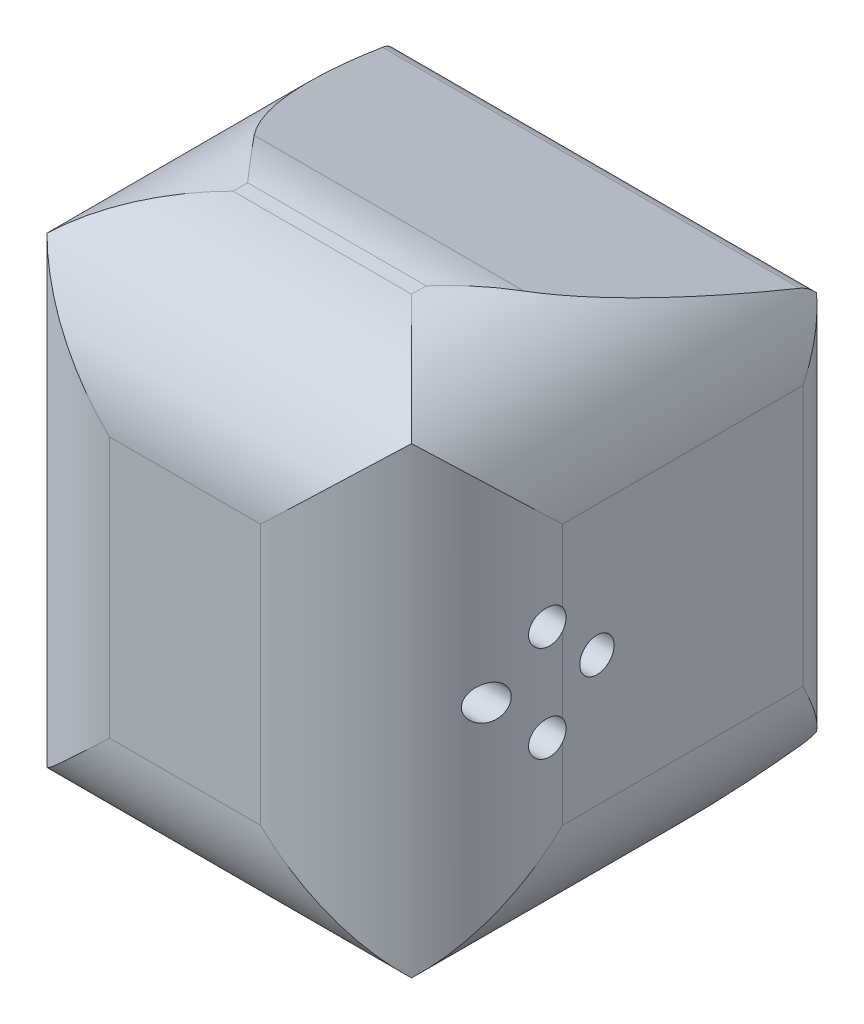
SolidWorks part; units mm, degrees
ref_plane "Front Plane" through (0, 0, 0) normal (0, 0, 1) x (1, 0, 0)
ref_plane "Top Plane" through (0, 0, 0) normal (0, 1, 0) x (1, 0, 0)
ref_plane "Right Plane" through (0, 0, 0) normal (1, 0, 0) x (0, 0, -1)
ref_plane "PX_m33_000" through (-33, 0, 0) normal (1, 0, 0) x (0, 0, -1)
sketch "S_prism1" plane through (-33, 0, 0) normal (1, 0, 0) x (0, 0, -1)
  line L0 (0, -25.0397) -> (0, 25.0397)
  line L1 (-2.8311, 28.8651) -> (-32.2859, 37.8651)
  line L2 (-39.8836, 39) -> (-42, 39)
  line L3 (-62, 19) -> (-62, -19)
  line L4 (-42, -39) -> (-39.8836, -39)
  line L5 (-32.2859, -37.8651) -> (-2.8311, -28.8651)
  arc A0 (-2.8311, -28.8651) -> (0, -25.0397) centre (-4.0002, -25.0395) ccw
  arc A1 (0, 25.0397) -> (-2.8311, 28.8651) centre (-4.0002, 25.0395) ccw
  arc A2 (-32.2859, 37.8651) -> (-39.8836, 39) centre (-39.8837, 12.9999) ccw
  arc A3 (-42, 39) -> (-62, 19) centre (-41.9999, 18.9999) ccw
  arc A4 (-62, -19) -> (-42, -39) centre (-41.9999, -18.9999) ccw
  arc A5 (-39.8836, -39) -> (-32.2859, -37.8651) centre (-39.8837, -12.9999) ccw
extrude "Boss_1" add sketch "S_prism1" along normal blind 66
ref_plane "PY_m40_000" through (0, -40, 0) normal (0, 1, 0) x (1, 0, 0)
sketch "S_pcut2" plane through (0, -40, 0) normal (0, 1, 0) x (1, 0, 0)
  line L0 (33.6, -62.6) -> (11, -62.6)
  line L1 (11, -62.6) -> (11, -62)
  line L2 (33, -40) -> (33.6, -40)
  line L3 (33.6, -40) -> (33.6, -62.6)
  arc A0 (11, -62) -> (33, -40) centre (10.9998, -39.9998) ccw
extrude "Cut_2" cut sketch "S_pcut2" along normal blind 80
sketch "S_pcut3" plane through (0, -40, 0) normal (0, 1, 0) x (1, 0, 0)
  line L0 (-33.6, -62.6) -> (-11, -62.6)
  line L1 (-11, -62.6) -> (-11, -62)
  line L2 (-33, -40) -> (-33.6, -40)
  line L3 (-33.6, -40) -> (-33.6, -62.6)
  arc A0 (-11, -62) -> (-33, -40) centre (-10.9998, -39.9998) cw
extrude "Cut_3" cut sketch "S_pcut3" along normal blind 80
sketch "S_pcut4" plane through (0, -40, 0) normal (0, 1, 0) x (1, 0, 0)
  line L0 (33.6, 0.6) -> (28, 0.6)
  line L1 (28, 0.6) -> (28, 0)
  line L2 (33, -5) -> (33.6, -5)
  line L3 (33.6, -5) -> (33.6, 0.6)
  arc A0 (28, 0) -> (33, -5) centre (27.9999, -5.0001) cw
extrude "Cut_4" cut sketch "S_pcut4" along normal blind 80
sketch "S_pcut5" plane through (0, -40, 0) normal (0, 1, 0) x (1, 0, 0)
  line L0 (-33.6, 0.6) -> (-28, 0.6)
  line L1 (-28, 0.6) -> (-28, 0)
  line L2 (-33, -5) -> (-33.6, -5)
  line L3 (-33.6, -5) -> (-33.6, 0.6)
  arc A0 (-28, 0) -> (-33, -5) centre (-27.9999, -5.0001) ccw
extrude "Cut_5" cut sketch "S_pcut5" along normal blind 80
ref_plane "PZ_m0_100" through (0, 0, -0.1) normal (0, 0, 1) x (1, 0, 0)
sketch "S_pcut6" plane through (0, 0, -0.1) normal (0, 0, 1) x (1, 0, 0)
  line L0 (33.6, 39.6) -> (13, 39.6)
  line L1 (13, 39.6) -> (13, 39)
  line L2 (33, 19) -> (33.6, 19)
  line L3 (33.6, 19) -> (33.6, 39.6)
  arc A0 (13, 39) -> (33, 19) centre (12.9999, 18.9999) cw
extrude "Cut_6" cut sketch "S_pcut6" along normal blind 62.2
sketch "S_pcut7" plane through (0, 0, -0.1) normal (0, 0, 1) x (1, 0, 0)
  line L0 (33.6, -39.6) -> (13, -39.6)
  line L1 (13, -39.6) -> (13, -39)
  line L2 (33, -19) -> (33.6, -19)
  line L3 (33.6, -19) -> (33.6, -39.6)
  arc A0 (13, -39) -> (33, -19) centre (12.9999, -18.9999) ccw
extrude "Cut_7" cut sketch "S_pcut7" along normal blind 62.2
sketch "S_pcut8" plane through (0, 0, -0.1) normal (0, 0, 1) x (1, 0, 0)
  line L0 (-33.6, 39.6) -> (-13, 39.6)
  line L1 (-13, 39.6) -> (-13, 39)
  line L2 (-33, 19) -> (-33.6, 19)
  line L3 (-33.6, 19) -> (-33.6, 39.6)
  arc A0 (-13, 39) -> (-33, 19) centre (-12.9999, 18.9999) ccw
extrude "Cut_8" cut sketch "S_pcut8" along normal blind 62.2
sketch "S_pcut9" plane through (0, 0, -0.1) normal (0, 0, 1) x (1, 0, 0)
  line L0 (-33.6, -39.6) -> (-13, -39.6)
  line L1 (-13, -39.6) -> (-13, -39)
  line L2 (-33, -19) -> (-33.6, -19)
  line L3 (-33.6, -19) -> (-33.6, -39.6)
  arc A0 (-13, -39) -> (-33, -19) centre (-12.9999, -18.9999) cw
extrude "Cut_9" cut sketch "S_pcut9" along normal blind 62.2
sketch "S_cut10" plane through (0, 0, -0.1) normal (0, 0, 1) x (1, 0, 0)
  line L0 (-26, -24) -> (26, -24)
  line L1 (26, -24) -> (26, 24)
  line L2 (26, 24) -> (-26, 24)
  line L3 (-26, 24) -> (-26, -24)
  dimension "P1" = 26
  dimension "P2" = 24
  dimension "P3" = 26
  dimension "P4" = 24
  dimension "P5" = 26
  dimension "P6" = 24
  dimension "P7" = 26
  dimension "P8" = 24
extrude "Pocket_10" cut sketch "S_cut10" along normal blind 16.2
ref_plane "PZ_p16_000" through (0, 0, 16) normal (0, 0, 1) x (1, 0, 0)
sketch "S_cut11" plane through (0, 0, 16) normal (0, 0, 1) x (1, 0, 0)
  line L0 (-26, -30) -> (26, -30)
  line L1 (26, -30) -> (26, 30)
  line L2 (26, 30) -> (-26, 30)
  line L3 (-26, 30) -> (-26, -30)
  dimension "P1" = 26
  dimension "P2" = 30
  dimension "P3" = 26
  dimension "P4" = 30
  dimension "P5" = 26
  dimension "P6" = 30
  dimension "P7" = 26
  dimension "P8" = 30
extrude "Pocket_11" cut sketch "S_cut11" along normal blind 36
ref_plane "PZ_p51_900" through (0, 0, 51.9) normal (0, 0, 1) x (1, 0, 0)
sketch "S_cut12" plane through (0, 0, 51.9) normal (0, 0, 1) x (1, 0, 0)
  line L0 (-18, -24) -> (18, -24)
  line L1 (18, -24) -> (18, 24)
  line L2 (18, 24) -> (-18, 24)
  line L3 (-18, 24) -> (-18, -24)
  dimension "P1" = 18
  dimension "P2" = 24
  dimension "P3" = 18
  dimension "P4" = 24
  dimension "P5" = 18
  dimension "P6" = 24
  dimension "P7" = 18
  dimension "P8" = 24
extrude "Pocket_12" cut sketch "S_cut12" along normal blind 6.1
sketch "S_cut13" plane through (0, 0, 16) normal (0, 0, 1) x (1, 0, 0)
  line L0 (-33.1, -16) -> (-25.9, -16)
  line L1 (-25.9, -16) -> (-25.9, 16)
  line L2 (-25.9, 16) -> (-33.1, 16)
  line L3 (-33.1, 16) -> (-33.1, -16)
  dimension "P1" = 33.1
  dimension "P2" = 16
  dimension "P3" = 25.9
  dimension "P4" = 16
  dimension "P5" = 25.9
  dimension "P6" = 16
  dimension "P7" = 33.1
  dimension "P8" = 16
extrude "Pocket_13" cut sketch "S_cut13" along normal blind 28
ref_plane "PX_p25_900" through (25.9, 0, 0) normal (1, 0, 0) x (0, 0, -1)
sketch "S_hole14" plane through (25.9, 0, 0) normal (1, 0, 0) x (0, 0, -1)
  circle A0 centre (-49, 0) radius 2.5
  dimension "D1_S_hole14" = 5
  dimension "P2" = 49
extrude "Hole_14" cut sketch "S_hole14" along normal blind 7.2
sketch "S_hole15" plane through (25.9, 0, 0) normal (1, 0, 0) x (0, 0, -1)
  circle A0 centre (-42, 7) radius 2.5
  dimension "D1_S_hole15" = 5
  dimension "P2" = 42
  dimension "P3" = 7
extrude "Hole_15" cut sketch "S_hole15" along normal blind 7.2
sketch "S_hole16" plane through (25.9, 0, 0) normal (1, 0, 0) x (0, 0, -1)
  circle A0 centre (-42, -7) radius 2.5
  dimension "D1_S_hole16" = 5
  dimension "P2" = 42
  dimension "P3" = 7
extrude "Hole_16" cut sketch "S_hole16" along normal blind 7.2
sketch "S_hole17" plane through (25.9, 0, 0) normal (1, 0, 0) x (0, 0, -1)
  circle A0 centre (-35, 0) radius 2.5
  dimension "D1_S_hole17" = 5
  dimension "P2" = 35
extrude "Hole_17" cut sketch "S_hole17" along normal blind 7.2
ref_plane "PX_m33_100" through (-33.1, 0, 0) normal (1, 0, 0) x (0, 0, -1)
sketch "S_hole18" plane through (-33.1, 0, 0) normal (1, 0, 0) x (0, 0, -1)
  circle A0 centre (-8, -10) radius 1.2
  dimension "D1_S_hole18" = 2.4
  dimension "P2" = 8
  dimension "P3" = 10
extrude "Hole_18" cut sketch "S_hole18" along normal blind 7.2
sketch "S_hole19" plane through (-33.1, 0, 0) normal (1, 0, 0) x (0, 0, -1)
  circle A0 centre (-8, -10) radius 2.3
  dimension "D1_S_hole19" = 4.6
  dimension "P2" = 8
  dimension "P3" = 10
extrude "Hole_19" cut sketch "S_hole19" along normal blind 2
sketch "S_hole20" plane through (-33.1, 0, 0) normal (1, 0, 0) x (0, 0, -1)
  circle A0 centre (-8, 10) radius 1.2
  dimension "D1_S_hole20" = 2.4
  dimension "P2" = 8
  dimension "P3" = 10
extrude "Hole_20" cut sketch "S_hole20" along normal blind 7.2
sketch "S_hole21" plane through (-33.1, 0, 0) normal (1, 0, 0) x (0, 0, -1)
  circle A0 centre (-8, 10) radius 2.3
  dimension "D1_S_hole21" = 4.6
  dimension "P2" = 8
  dimension "P3" = 10
extrude "Hole_21" cut sketch "S_hole21" along normal blind 2
equation "\"plate_t\" = 3"
equation "\"clearance\" = 0.5"
